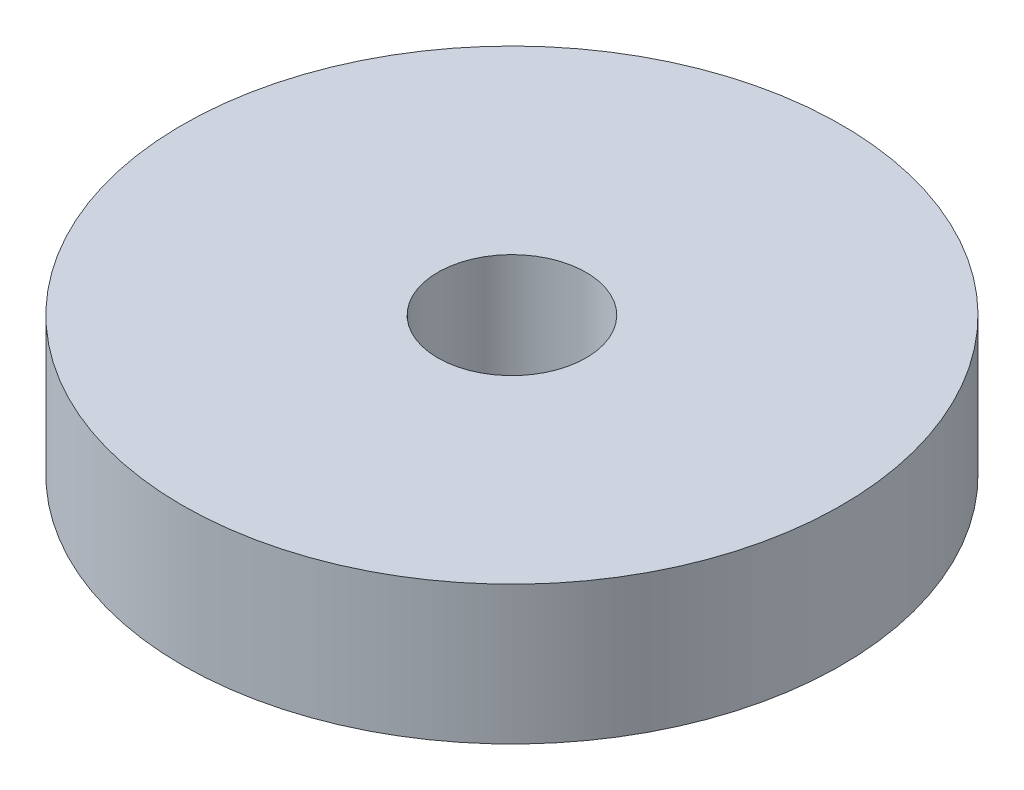
SolidWorks part; units mm, degrees
ref_plane "Front Plane" through (0, 0, 0) normal (0, 0, 1) x (1, 0, 0)
ref_plane "Top Plane" through (0, 0, 0) normal (0, 1, 0) x (1, 0, 0)
ref_plane "Right Plane" through (0, 0, 0) normal (1, 0, 0) x (0, 0, -1)
sketch "Sketch1" plane through (0, 0, 0) normal (0, 1, 0) x (1, 0, 0)
  circle A0 centre (0, 0) radius 10
  dimension "D1" = 20
extrude "Boss-Extrude1" add sketch "Sketch1" along normal blind 4.2
hole_wizard "M4 Clearance Hole1" positions "Sketch2" profile "Sketch3" hole size "M4" standard "ANSI Metric" end condition through all
sketch "Sketch2" plane through (0, 4.2, 0) normal (0, 1, 0) x (1, 0, 0)
  point P0 (0, 0)
sketch "Sketch3" plane through (0, 4.2, 0) normal (1, 0, 0) x (0, 0, 1)
  line L0 (0, 0) -> (0, 4.2)
  line L1 (0, 4.2) -> (2.25, 4.2)
  line L2 (2.25, 4.2) -> (2.25, 0)
  line L5 (2.25, 0) -> (0, 0)
  line L11 (0, -6.35) -> (0, 107.95) construction
  dimension "Thru Hole Dia." = 4.5
  dimension "Thru Hole Depth" = 4.2
